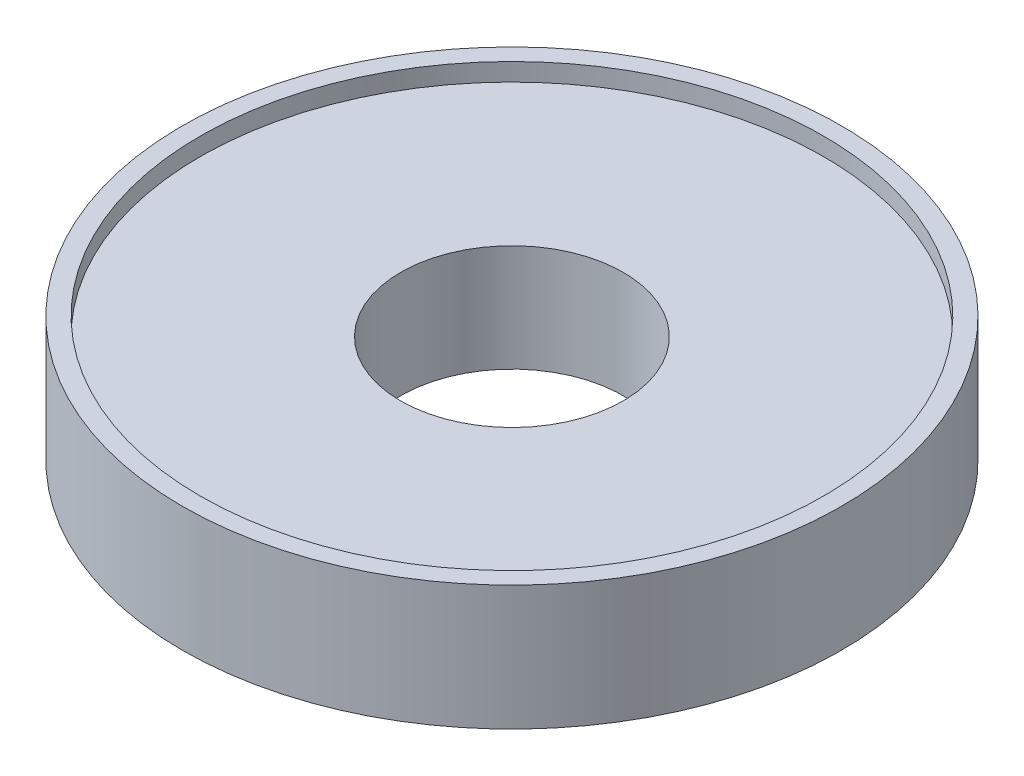
SolidWorks part; units mm, degrees
ref_plane "Front Plane" through (0, 0, 0) normal (0, 0, 1) x (1, 0, 0)
ref_plane "Top Plane" through (0, 0, 0) normal (0, 1, 0) x (1, 0, 0)
ref_plane "Right Plane" through (0, 0, 0) normal (1, 0, 0) x (0, 0, -1)
sketch "Sketch1" plane through (0, 0, 0) normal (0, 1, 0) x (1, 0, 0)
  circle A0 centre (0, 0) radius 18.5
  circle A1 centre (0, 0) radius 17.5 construction
  dimension "D1" = 35
  dimension "D2" = 1
extrude "Boss-Extrude1" add sketch "Sketch1" along normal blind 6
sketch "Sketch2" plane through (0, 6, 0) normal (0, 1, 0) x (1, 0, 0)
  circle A0 centre (0, 0) radius 17.5 construction
  circle A1 centre (0, 0) radius 17.5
  circle A2 centre (0, 0) radius 18.5 construction
  circle A3 centre (0, 0) radius 18.5
extrude "Boss-Extrude2" add sketch "Sketch2" along normal blind 1
hole_wizard "M14x1.5 Tapped Hole1" positions "Sketch3" profile "Sketch4" tap size "M14x1.5" standard "ANSI Metric" end condition through all
sketch "Sketch3" plane through (0, 6, 0) normal (0, 1, 0) x (1, 0, 0)
  point P0 (0, 0)
sketch "Sketch4" plane through (0, 6, 0) normal (1, 0, 0) x (0, 0, 1)
  line L0 (0, 0) -> (0, 6)
  line L1 (0, 6) -> (6.25, 6)
  line L2 (6.25, 6) -> (6.25, 0)
  line L5 (6.25, 0) -> (0, 0)
  line L11 (0, -6.35) -> (0, 107.95) construction
  dimension "Thru Tap Drill Dia." = 12.5
  dimension "Thru Tap Drill Depth" = 6
sketch "Sketch5" plane through (0, 0, 0) normal (0, -1, 0) x (1, 0, 0)
  line L1 (10.6066, -10.6066) -> (-10.6066, -10.6066) construction
  line L2 (10.6066, -10.6066) -> (10.6066, 10.6066) construction
  line L3 (10.6066, 10.6066) -> (-10.6066, 10.6066) construction
  line L4 (-10.6066, -10.6066) -> (-10.6066, 10.6066) construction
  line L5 (10.6066, -10.6066) -> (-10.6066, 10.6066) construction
  line L6 (10.6066, 10.6066) -> (-10.6066, -10.6066) construction
  circle A0 centre (-10.6066, 10.6066) radius 1.5
  circle A1 centre (10.6066, 10.6066) radius 1.5
  circle A2 centre (10.6066, -10.6066) radius 1.5
  circle A3 centre (-10.6066, -10.6066) radius 1.5
  point P0 (0, 0)
  dimension "D2" = 3
  dimension "D1" = 30
extrude "Cut-Extrude1" cut sketch "Sketch5" against normal blind 4
